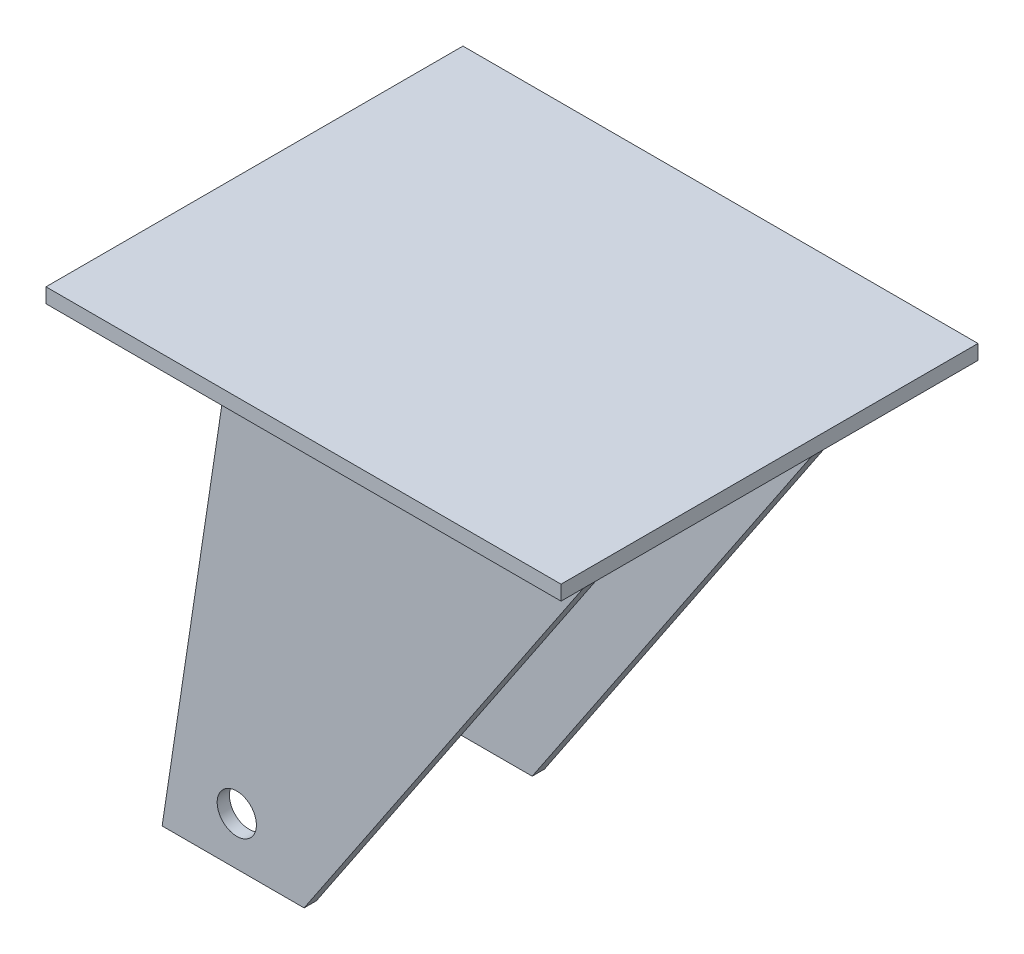
SolidWorks part; units mm, degrees
ref_plane "Спереди" through (0, 0, 0) normal (0, 0, 1) x (1, 0, 0)
ref_plane "Сверху" through (0, 0, 0) normal (0, 1, 0) x (1, 0, 0)
ref_plane "Справа" through (0, 0, 0) normal (1, 0, 0) x (0, 0, -1)
sketch "Sketch1" plane through (0, 0, 0) normal (0, 1, 0) x (1, 0, 0)
  line L1 (46.437, 67.9814) -> (-58.563, 67.9814)
  line L2 (46.437, 67.9814) -> (46.437, 152.9814)
  line L3 (46.437, 152.9814) -> (-58.563, 152.9814)
  line L4 (-58.563, 67.9814) -> (-58.563, 152.9814)
  line L5 (46.437, 67.9814) -> (-58.563, 152.9814) construction
  line L6 (46.437, 152.9814) -> (-58.563, 67.9814) construction
  point P0 (-6.063, 110.4814)
extrude "Boss-Extrude1" add sketch "Sketch1" along normal blind 3 separate body
ref_plane "Plane1" through (0, 0, -134.9814) normal (0, 0, -1) x (-1, 0, 0)
ref_plane "Plane2" through (0, 0, -85.9814) normal (0, 0, 1) x (1, 0, 0)
sketch "Sketch3" plane through (0, 0, -85.9814) normal (0, 0, 1) x (1, 0, 0)
  line L0 (-38, 0) -> (42, 0)
  line L1 (42, 0) -> (-23.9461, -98.3523)
  line L2 (-23.9461, -98.3523) -> (-52.8846, -98.3523)
  line L3 (-58.563, 0) -> (46.437, 0) construction
  line L4 (-52.8846, -98.3523) -> (-38, 0)
extrude "Boss-Extrude3" add sketch "Sketch3" against normal blind 2.5
sketch "Sketch2" plane through (0, 0, -134.9814) normal (0, 0, -1) x (-1, 0, 0)
  line L0 (38, 0) -> (52.8846, -98.3523)
  line L1 (52.8846, -98.3523) -> (23.9461, -98.3523)
  line L2 (23.9461, -98.3523) -> (-42, 0)
  line L4 (-42, 0) -> (38, 0)
extrude "Boss-Extrude2" add sketch "Sketch2" against normal blind 2.5
sketch "Sketch4" plane through (0, 0, -134.9814) normal (0, 0, -1) x (-1, 0, 0)
  circle A0 centre (37.67, -88.5743) radius 4
extrude "Cut-Extrude1" cut sketch "Sketch4" against normal through all
